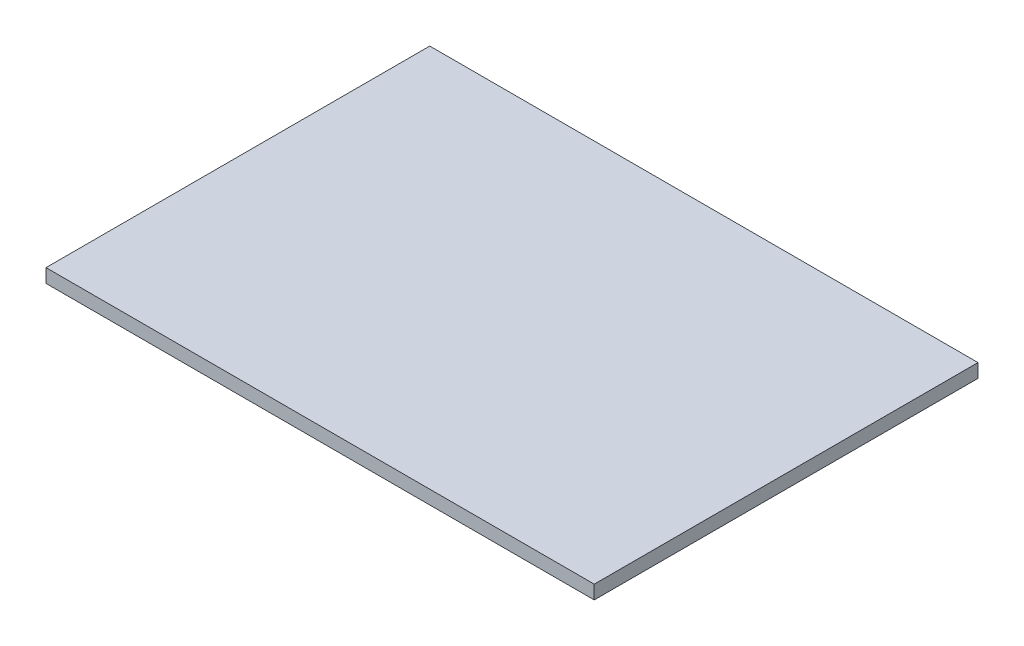
SolidWorks part; units mm, degrees
ref_plane "Front Plane" through (0, 0, 0) normal (0, 0, 1) x (1, 0, 0)
ref_plane "Top Plane" through (0, 0, 0) normal (0, 1, 0) x (1, 0, 0)
ref_plane "Right Plane" through (0, 0, 0) normal (1, 0, 0) x (0, 0, -1)
sketch "Sketch1" plane through (0, 0, 0) normal (0, 1, 0) x (1, 0, 0)
  line L1 (0, 0) -> (508, 0)
  line L2 (0, 0) -> (0, 355.6)
  line L3 (0, 355.6) -> (508, 355.6)
  line L4 (508, 0) -> (508, 355.6)
  dimension "D1" = 355.6
  dimension "D2" = 508
extrude "Boss-Extrude1" add sketch "Sketch1" along normal blind 12.7
